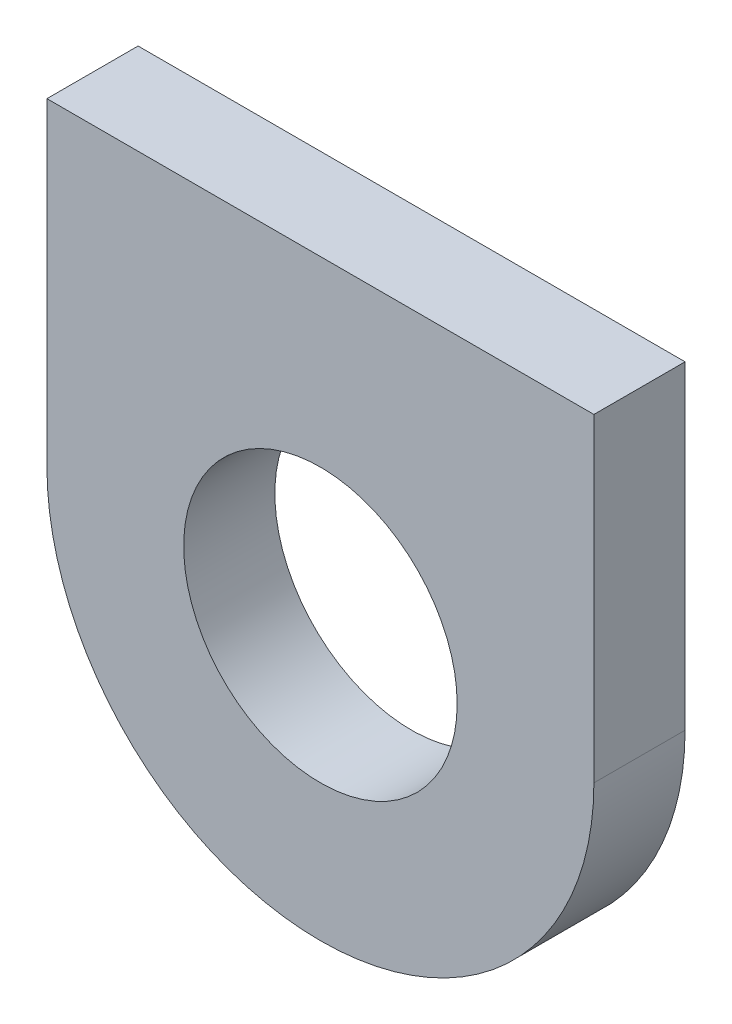
SolidWorks part; units mm, degrees
ref_plane "Front Plane" through (0, 0, 0) normal (0, 0, 1) x (1, 0, 0)
ref_plane "Top Plane" through (0, 0, 0) normal (0, 1, 0) x (1, 0, 0)
ref_plane "Right Plane" through (0, 0, 0) normal (1, 0, 0) x (0, 0, -1)
sketch "Sketch1" plane through (0, 0, 0) normal (0, 0, 1) x (1, 0, 0)
  line L0 (-30, 0) -> (-30, 35)
  line L1 (-30, 35) -> (30, 35)
  line L2 (30, 35) -> (30, 0)
  circle A0 centre (0, 0) radius 15
  arc A1 (-30, 0) -> (30, 0) centre (0, 0) ccw
  circle A3 centre (0, 0) radius 30 construction
  point P8 (30, 0)
  dimension "D1" = 30
  dimension "D3" = 35
  dimension "D2" = 15
extrude "Boss-Extrude1" add sketch "Sketch1" along normal blind 10
